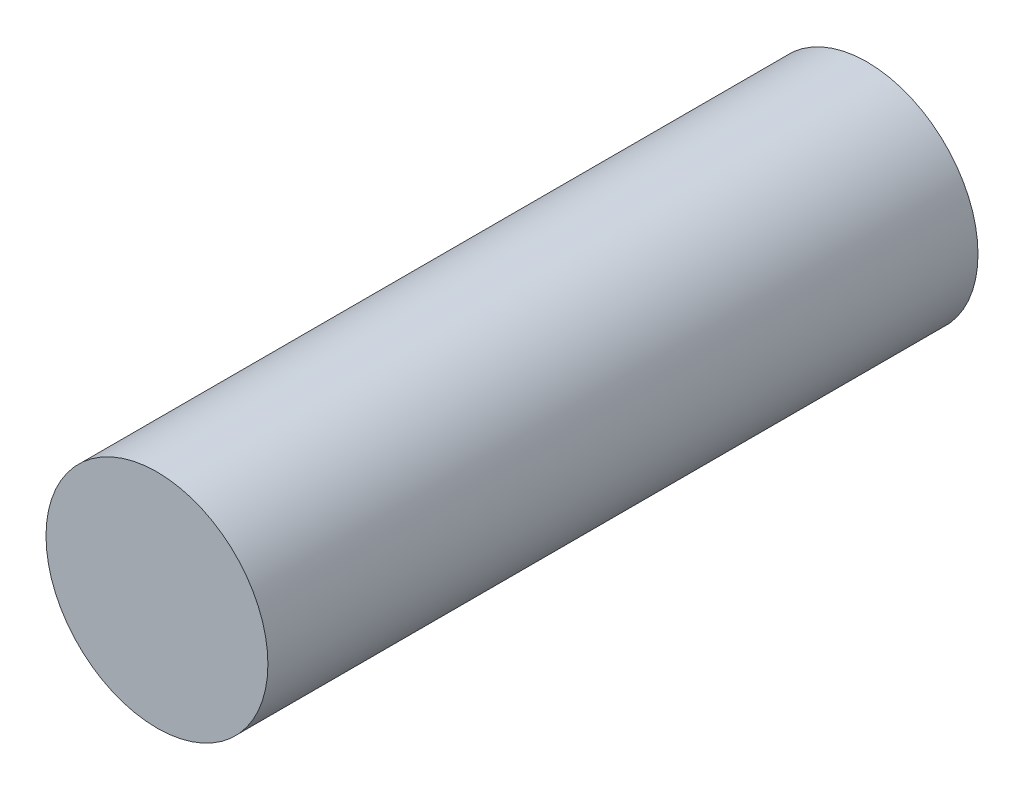
SolidWorks part; units mm, degrees
ref_plane "Front Plane" through (0, 0, 0) normal (0, 0, 1) x (1, 0, 0)
ref_plane "Top Plane" through (0, 0, 0) normal (0, 1, 0) x (1, 0, 0)
ref_plane "Right Plane" through (0, 0, 0) normal (1, 0, 0) x (0, 0, -1)
sketch "Sketch1" plane through (0, 0, 0) normal (0, 0, 1) x (1, 0, 0)
  circle A0 centre (6780.7758, 3567.9681) radius 1.5875
extrude "Boss-Extrude1" add sketch "Sketch1" along normal blind 10.16
